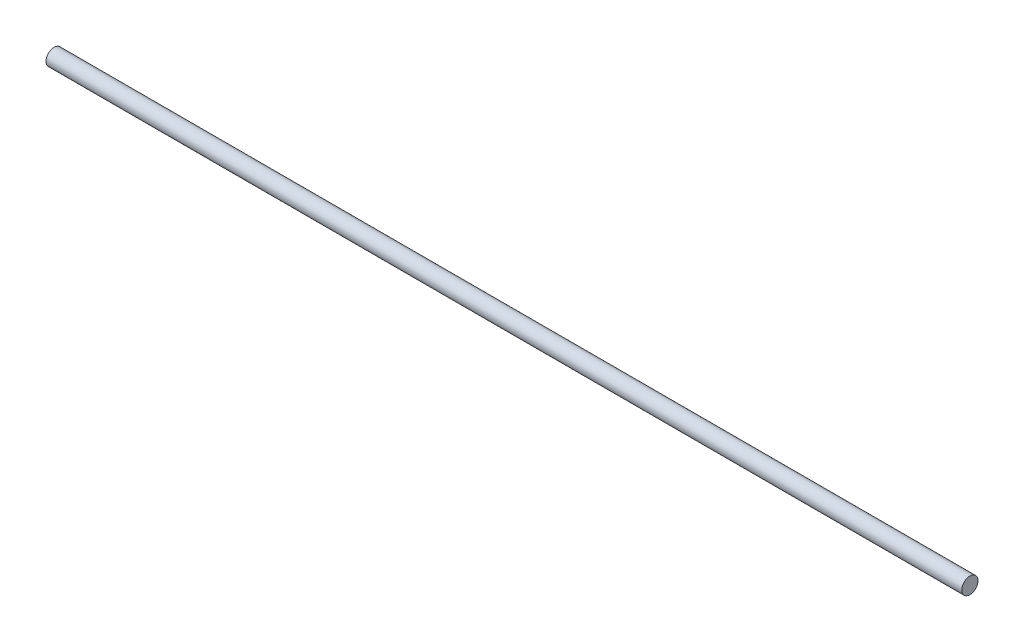
SolidWorks part; units mm, degrees
ref_plane "Front Plane" through (0, 0, 0) normal (0, 0, 1) x (1, 0, 0)
ref_plane "Top Plane" through (0, 0, 0) normal (0, 1, 0) x (1, 0, 0)
ref_plane "Right Plane" through (0, 0, 0) normal (1, 0, 0) x (0, 0, -1)
sketch "Sketch1" plane through (0, 0, 0) normal (1, 0, 0) x (0, 0, -1)
  circle A0 centre (0, 0) radius 2.5
  dimension "D1" = 5
extrude "Boss-Extrude1" add sketch "Sketch1" along normal blind 282
